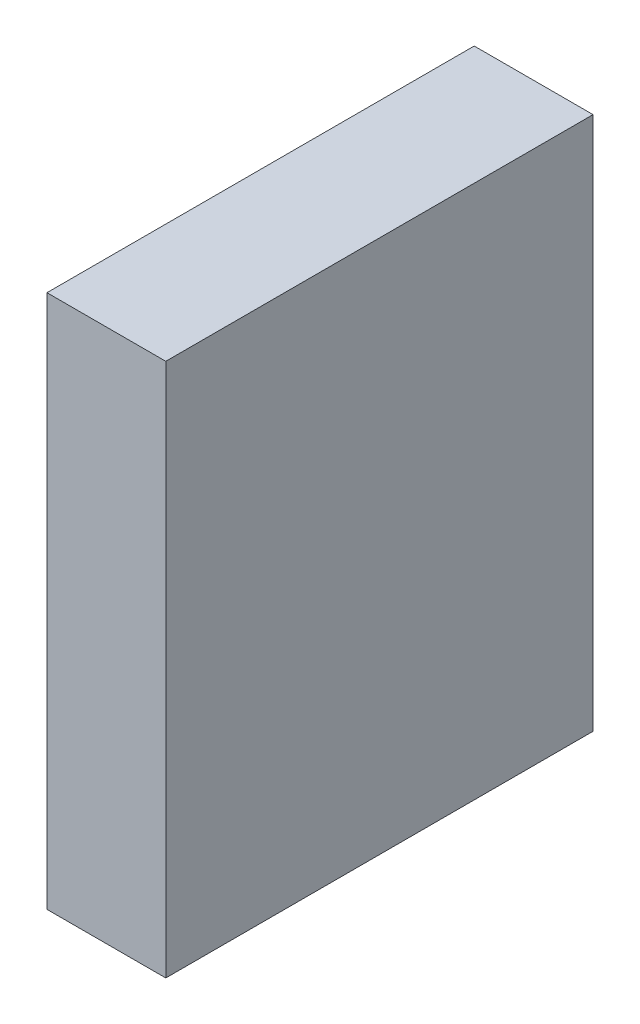
SolidWorks part; units mm, degrees
ref_plane "Front Plane" through (0, 0, 0) normal (0, 0, 1) x (1, 0, 0)
ref_plane "Top Plane" through (0, 0, 0) normal (0, 1, 0) x (1, 0, 0)
ref_plane "Right Plane" through (0, 0, 0) normal (1, 0, 0) x (0, 0, -1)
sketch "Sketch1" plane through (0, 0, 0) normal (1, 0, 0) x (0, 0, -1)
  line L1 (-51.9208, 41.7052) -> (28.0792, 41.7052)
  line L2 (-51.9208, 41.7052) -> (-51.9208, -58.2948)
  line L3 (-51.9208, -58.2948) -> (28.0792, -58.2948)
  line L4 (28.0792, 41.7052) -> (28.0792, -58.2948)
  dimension "D1" = 80
  dimension "D2" = 100
extrude "Boss-Extrude1" add sketch "Sketch1" against normal blind 22.25
